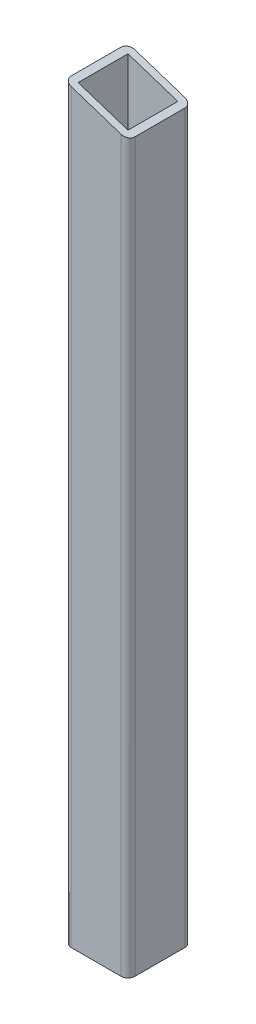
SolidWorks part; units mm, degrees
ref_plane "Front Plane" through (0, 0, 0) normal (0, 0, 1) x (1, 0, 0)
ref_plane "Top Plane" through (0, 0, 0) normal (0, 1, 0) x (1, 0, 0)
ref_plane "Right Plane" through (0, 0, 0) normal (1, 0, 0) x (0, 0, -1)
sketch "Sketch1" plane through (0, 0, 0) normal (0, 1, 0) x (1, 0, 0)
  line L1 (2.8, 0) -> (22.8, 0)
  line L2 (0, -2.8) -> (0, -22.8)
  line L3 (2.8, -25.6) -> (22.8, -25.6)
  line L4 (25.6, -2.8) -> (25.6, -22.8)
  arc A0 (22.8, 0) -> (25.6, -2.8) centre (22.8, -2.8) cw
  arc A1 (22.8, -25.6) -> (25.6, -22.8) centre (22.8, -22.8) ccw
  arc A2 (0, -22.8) -> (2.8, -25.6) centre (2.8, -22.8) ccw
  arc A3 (2.8, 0) -> (0, -2.8) centre (2.8, -2.8) ccw
  point P7 (25.6, 0)
  point P10 (25.6, -25.6)
  point P15 (0, 0)
  dimension "D2" = 2.8
  dimension "D1" = 25.6
extrude "Boss-Extrude1" add sketch "Sketch1" along normal blind 300.25
sketch "Sketch3" plane through (0, 0, 0) normal (0, -1, 0) x (-1, 0, 0)
  line L4 (-2.8, -2.8) -> (-22.8, -2.8)
  line L5 (-2.8, -2.8) -> (-2.8, -22.8)
  line L6 (-2.8, -22.8) -> (-22.8, -22.8)
  line L7 (-22.8, -2.8) -> (-22.8, -22.8)
  line L8 (-2.8, -2.8) -> (-22.8, -22.8) construction
  line L9 (-2.8, -22.8) -> (-22.8, -2.8) construction
  point P6 (-12.8, -12.8)
extrude "Cut-Extrude1" cut sketch "Sketch3" against normal blind 1040.5
ref_plane "Plane1" through (0, 0, 22.8) normal (0, 0, 1) x (1, 0, 0)
sketch "Sketch4" plane through (0, 0, 22.8) normal (0, 0, 1) x (1, 0, 0)
  line L0 (0, 300.25) -> (25.6, 291.8628)
  line L1 (25.6, 300.25) -> (25.6, 0) construction
extrude "Cut-Extrude2" cut sketch "Sketch4" against normal through all and the other way through all
